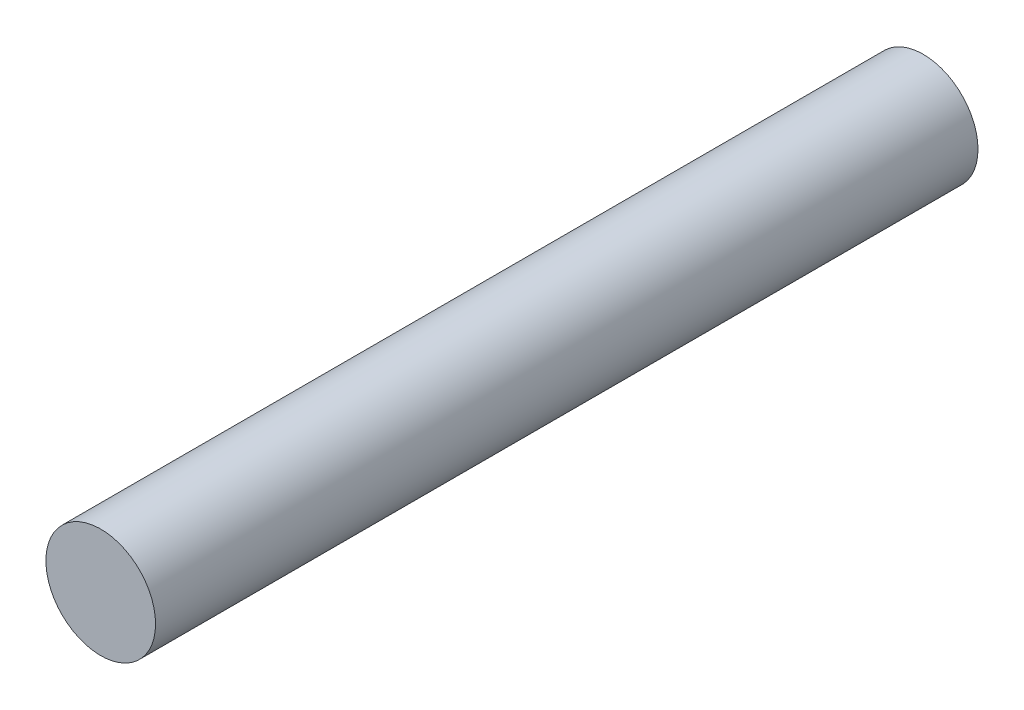
SolidWorks part; units mm, degrees
ref_plane "Plan de face" through (0, 0, 0) normal (0, 0, 1) x (1, 0, 0)
ref_plane "Plan de dessus" through (0, 0, 0) normal (0, 1, 0) x (1, 0, 0)
ref_plane "Plan de droite" through (0, 0, 0) normal (1, 0, 0) x (0, 0, -1)
sketch "Esquisse1" plane through (0, 0, 0) normal (0, 0, 1) x (1, 0, 0)
  circle A0 centre (0, 0) radius 10
  dimension "D1" = 20
extrude "Boss.-Extru.1" add sketch "Esquisse1" along normal blind 150
